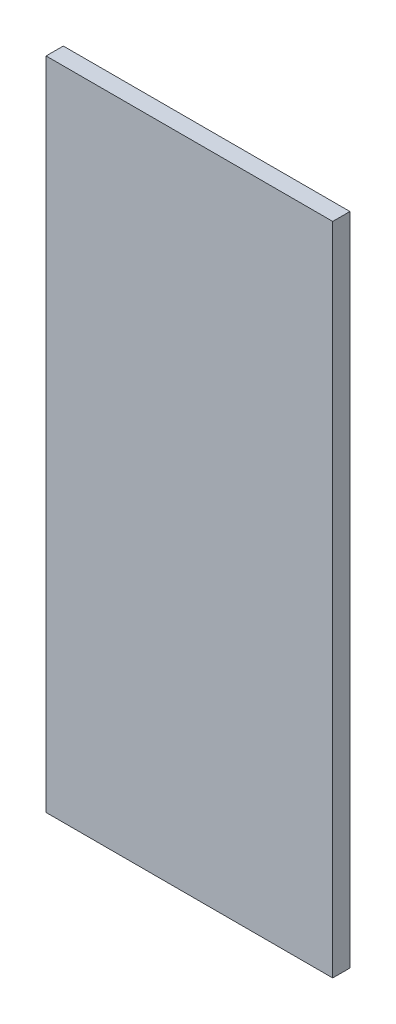
SolidWorks part; units mm, degrees
ref_plane "Front Plane" through (0, 0, 0) normal (0, 0, 1) x (1, 0, 0)
ref_plane "Top Plane" through (0, 0, 0) normal (0, 1, 0) x (1, 0, 0)
ref_plane "Right Plane" through (0, 0, 0) normal (1, 0, 0) x (0, 0, -1)
sketch "Sketch1" plane through (0, 0, 0) normal (0, 0, 1) x (1, 0, 0)
  line L1 (25, -57.15) -> (-25, -57.15)
  line L2 (25, -57.15) -> (25, 57.15)
  line L3 (25, 57.15) -> (-25, 57.15)
  line L4 (-25, -57.15) -> (-25, 57.15)
  line L5 (25, -57.15) -> (-25, 57.15) construction
  line L6 (25, 57.15) -> (-25, -57.15) construction
  point P0 (0, 0)
  dimension "D1" = 114.3
  dimension "D2" = 50
extrude "Boss-Extrude1" add sketch "Sketch1" along normal blind 3
